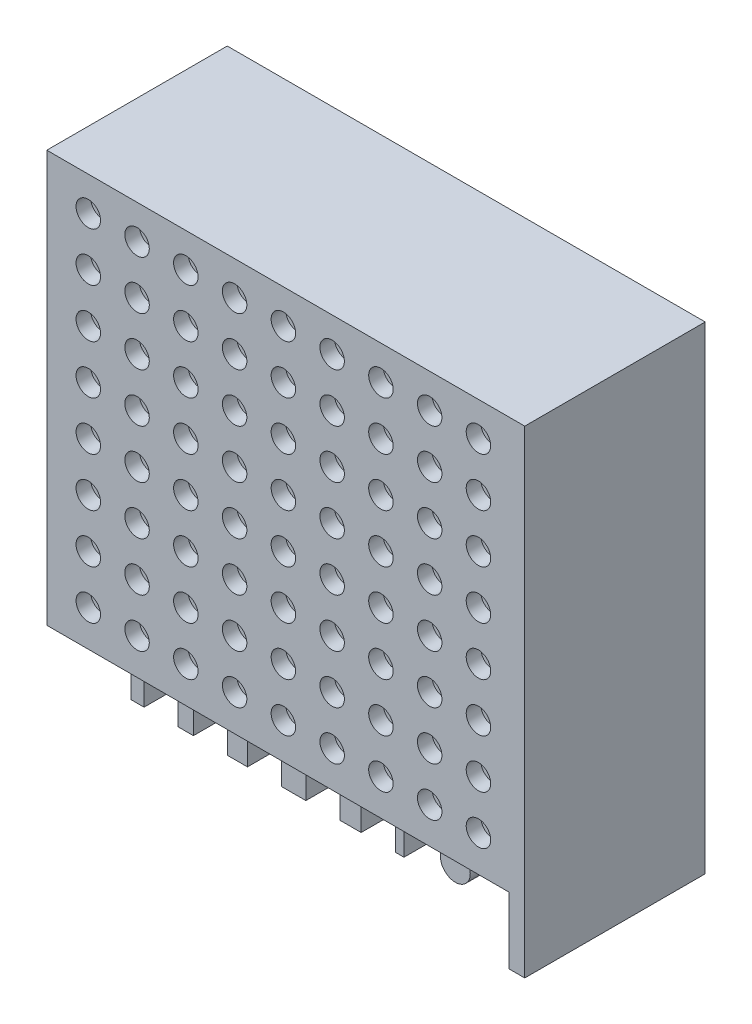
SolidWorks part; units mm, degrees
ref_plane "前视基准面" through (0, 0, 0) normal (0, 0, 1) x (1, 0, 0)
ref_plane "上视基准面" through (0, 0, 0) normal (0, 1, 0) x (1, 0, 0)
ref_plane "右视基准面" through (0, 0, 0) normal (1, 0, 0) x (0, 0, -1)
sketch "草图1" plane through (0, 0, 0) normal (0, 0, 1) x (1, 0, 0)
  line L0 (0, 0) -> (0, 55.2358) construction
  line L1 (-49, 49) -> (49, 49)
  line L2 (-49, 49) -> (-49, -49)
  line L3 (-49, -49) -> (49, -49)
  line L4 (49, 49) -> (49, -49)
  line L5 (0, 0) -> (66.5086, 0) construction
  dimension "D1" = 98
  dimension "D2" = 98
extrude "凸台-拉伸1" add sketch "草图1" along normal blind 37
sketch "草图2" plane through (0, 0, 37) normal (0, 0, 1) x (1, 0, 0)
  line L1 (-49, -49) -> (45.797, -49)
  line L2 (-49, -49) -> (-49, -35.3691)
  line L3 (-49, -35.3691) -> (45.797, -35.3691)
  line L4 (45.797, -49) -> (45.797, -35.3691)
extrude "切除-拉伸1" cut sketch "草图2" against normal blind 15
sketch "草图3" plane through (0, 0, 22) normal (0, 0, 1) x (1, 0, 0)
  line L1 (-38.6955, -38.5901) -> (17.2376, -38.5901)
  line L2 (-38.6955, -38.5901) -> (-38.6955, -46.9419)
  line L3 (-38.6955, -46.9419) -> (17.2376, -46.9419)
  line L4 (17.2376, -38.5901) -> (17.2376, -46.9419)
  circle A0 centre (27.7681, -43.0615) radius 3.0612
extrude "凸台-拉伸2" add sketch "草图3" along normal blind 8
sketch "草图4" plane through (0, 0, 30) normal (0, 0, 1) x (1, 0, 0)
  line L0 (17.2376, -38.5901) -> (-38.6955, -38.5901) construction
  line L1 (-36.061, -38.5901) -> (-29.061, -38.5901)
  line L2 (-36.061, -38.5901) -> (-36.061, -46.9419)
  line L3 (-36.061, -46.9419) -> (-29.061, -46.9419)
  line L4 (-29.061, -38.5901) -> (-29.061, -46.9419)
  line L5 (-38.6955, -46.9419) -> (17.2376, -46.9419) construction
  line L6 (17.2376, -38.5901) -> (-38.6955, -38.5901) construction
  line L7 (-25.9409, -38.5901) -> (-18.9409, -38.5901)
  line L8 (-25.9409, -38.5901) -> (-25.9409, -46.9419)
  line L9 (-25.9409, -46.9419) -> (-18.9409, -46.9419)
  line L10 (-18.9409, -38.5901) -> (-18.9409, -46.9419)
  line L11 (-14.8531, -38.5901) -> (-7.8531, -38.5901)
  line L12 (-14.8531, -38.5901) -> (-14.8531, -46.9419)
  line L13 (-14.8531, -46.9419) -> (-7.8531, -46.9419)
  line L14 (-7.8531, -38.5901) -> (-7.8531, -46.9419)
  line L16 (-2.8825, -38.5901) -> (4.1175, -38.5901)
  line L17 (-2.8825, -38.5901) -> (-2.8825, -46.9419)
  line L18 (-2.8825, -46.9419) -> (4.1175, -46.9419)
  line L19 (4.1175, -38.5901) -> (4.1175, -46.9419)
  line L20 (8.453, -38.5901) -> (15.453, -38.5901)
  line L21 (8.453, -38.5901) -> (8.453, -46.9419)
  line L22 (8.453, -46.9419) -> (15.453, -46.9419)
  line L23 (15.453, -38.5901) -> (15.453, -46.9419)
  dimension "D1" = 7
extrude "切除-拉伸2" cut sketch "草图4" against normal blind 5
sketch "草图5" plane through (0, 0, 25) normal (0, 0, 1) x (1, 0, 0)
  circle A0 centre (-32.652, -42.6771) radius 1.9637
  circle A1 centre (-22.1221, -42.6771) radius 2.092
  circle A2 centre (-11.5226, -42.6771) radius 2.1482
  circle A3 centre (0, -42.6771) radius 2.1891
  circle A4 centre (11.8802, -42.6771) radius 2.3135
extrude "凸台-拉伸3" add sketch "草图5" along normal blind 1.5
hole_wizard "M3x0.5 螺纹孔1" positions "草图7" profile "草图6" tap size "M3x0.5" standard "JIS"
sketch "草图7" plane through (0, 0, 0) normal (0, 0, -1) x (-1, 0, 0)
  line L0 (-49, -49) -> (-49, 49) construction
  line L1 (-49, 49) -> (49, 49) construction
  point P1 (-3, 25)
  point P3 (-3, -30)
  dimension "D1" = 46
  dimension "D2" = 55
  dimension "D3" = 24
sketch "草图6" plane through (3, 25, 0) normal (1, 0, 0) x (0, 1, 0)
  line L0 (0, 0) -> (0, 8.2511)
  line L1 (0, 8.2511) -> (1.25, 7.5)
  line L2 (1.25, 7.5) -> (1.25, 0)
  line L5 (1.25, 0) -> (0, 0)
  line L10 (0, 8.2511) -> (-1.25, 7.5) construction
  line L11 (0, -6.35) -> (0, 107.95) construction
  dimension "螺纹孔钻头直径" = 2.5
  dimension "螺纹孔钻头深度" = 7.5
  dimension "导头角度" = 118
cosmetic thread "孔螺蚊线1" parameters "D1"=6, "D2"=3
cosmetic thread "孔螺蚊线2" parameters "D1"=6, "D2"=3
sketch "草图8" plane through (0, 0, 37) normal (0, 0, 1) x (1, 0, 0)
  circle A0 centre (-40.4935, 42.0164) radius 2.5084
extrude "切除-拉伸3" cut sketch "草图8" against normal blind 3
pattern_linear "阵列(线性)1" count 9 spacing 10 along (1, 0, 0) count 8 spacing 10 along (0, -1, 0) of "切除-拉伸3"
